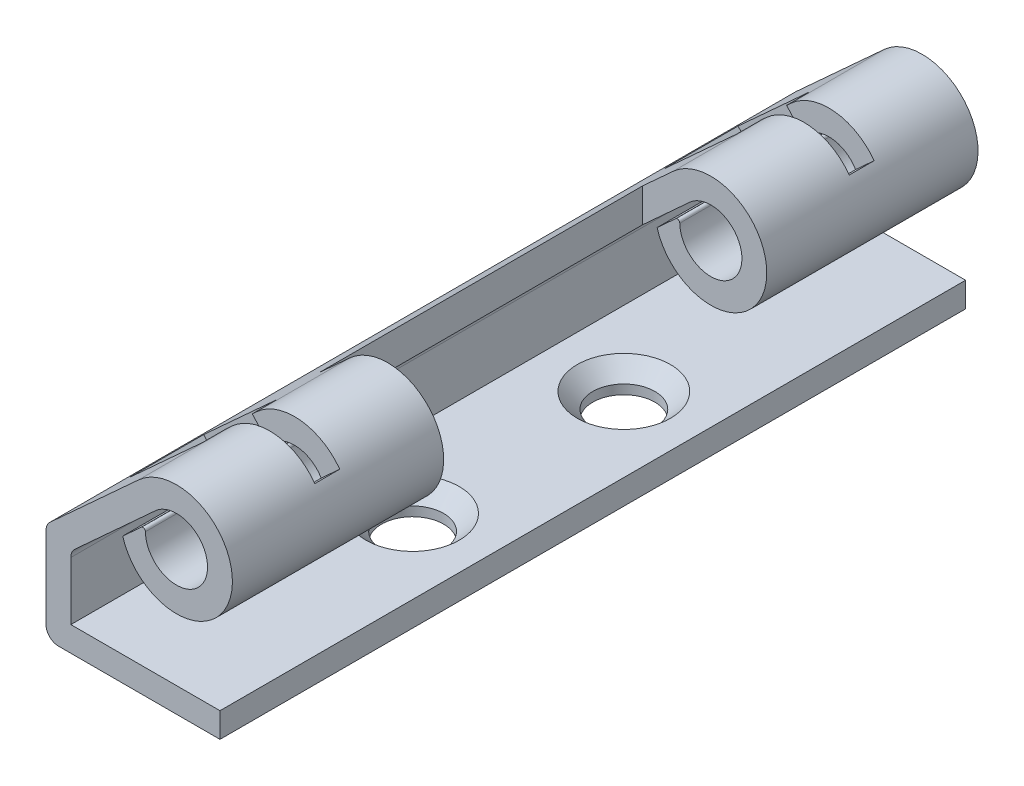
SolidWorks part; units mm, degrees
ref_plane "前视基准面" through (0, 0, 0) normal (0, 0, 1) x (1, 0, 0)
ref_plane "上视基准面" through (0, 0, 0) normal (0, 1, 0) x (1, 0, 0)
ref_plane "右视基准面" through (0, 0, 0) normal (1, 0, 0) x (0, 0, -1)
sketch "草图1" plane through (0, 0, 0) normal (0, 0, 1) x (1, 0, 0)
  line L0 (0, 0) -> (-13, 0)
  line L1 (-14, 1) -> (-14, 7.5592)
  line L2 (-13.6746, 8.2974) -> (-6.5358, 14.8217)
  line L3 (0, 2) -> (-12, 2)
  line L4 (-12, 2) -> (-12, 6.6776)
  line L5 (-11.6746, 7.4158) -> (-5.1866, 13.3454)
  line L6 (0, 2) -> (0, 0)
  line L7 (-7.8249, 10.2568) -> (-6.3348, 11.6187)
  line L8 (-12, 2) -> (-12, 7.1184) construction
  line L9 (-12, 7.1184) -> (-5.1866, 13.3454) construction
  line L10 (-14, 0) -> (-14, 8) construction
  line L11 (-14, 8) -> (-6.5358, 14.8217) construction
  line L12 (0, 0) -> (-14, 0) construction
  arc A0 (-7.8249, 10.2568) -> (-6.5358, 14.8217) centre (-3.5, 11.5) ccw
  arc A1 (-5.9999, 11.4732) -> (-5.1866, 13.3454) centre (-3.5, 11.5) ccw
  circle A2 centre (-3.5, 11.5) radius 2.5 construction
  circle A3 centre (-3.5, 11.5) radius 4.5 construction
  arc A4 (-6.3348, 11.6187) -> (-5.9999, 11.4732) centre (-6.1998, 11.471) cw
  arc A5 (-12, 6.6776) -> (-11.6746, 7.4158) centre (-11, 6.6776) cw
  arc A6 (-14, 7.5592) -> (-13.6746, 8.2974) centre (-13, 7.5592) cw
  arc A7 (-13, 0) -> (-14, 1) centre (-13, 1) cw
  point P7 (-3.5, 16)
  point P8 (1, 11.5)
  point P25 (-14, 8)
  dimension "D4" = 9
  dimension "D8" = 0.2
  dimension "D9" = 1
  dimension "D10" = 1
  dimension "D2" = 16
  dimension "D3" = 14
  dimension "D5" = 15
  dimension "D6" = 0.5
  dimension "D11" = 8
  dimension "D7" = 2
extrude "凸台-拉伸1" add sketch "草图1" along normal mid plane 60
sketch "草图2" plane through (0, 2, 0) normal (0, 1, 0) x (1, 0, 0)
  line L0 (1, -30) -> (1, 30) construction
  line L1 (1, 13) -> (-9, 13)
  line L2 (1, 13) -> (1, -13)
  line L3 (1, -13) -> (-9, -13)
  line L4 (-9, 13) -> (-9, -13)
  line L5 (-7.8249, -30) -> (1, -30) construction
  line L6 (1, 30) -> (-7.8249, 30) construction
  line L7 (-14, -30) -> (-14, 30) construction
  dimension "D1" = 17
  dimension "D2" = 17
  dimension "D3" = 5
extrude "切除-拉伸1" cut sketch "草图2" along normal up to next
hole_wizard "打孔尺寸(%根据十字)槽沉头木螺钉的类型1" positions "草图4" profile "草图3" countersink size "M4" standard "GB" end condition through all
sketch "草图4" plane through (0, 2, 0) normal (0, 1, 0) x (1, 0, 0)
  line L0 (0, -30) -> (0, 30) construction
  line L1 (0, 0) -> (-9, 0) construction
  line L2 (-9, -13) -> (-9, 13) construction
  point P0 (-6, 8.5)
  point P2 (-6, -8.5)
  dimension "D1" = 17
  dimension "D2" = 6
sketch "草图3" plane through (-6, 2, -8.5) normal (1, 0, 0) x (0, 0, 1)
  line L0 (0, 0) -> (0, 2)
  line L1 (0, 2) -> (2.5, 2)
  line L2 (2.5, 2) -> (2.5, 1.25)
  line L3 (2.5, 1.25) -> (3.75, 0)
  line L5 (3.75, 0) -> (0, 0)
  line L6 (-2.5, 1.25) -> (-3.75, 0) construction
  line L11 (0, -6.35) -> (0, 107.95) construction
  dimension "通孔孔直径" = 5
  dimension "通孔孔深度" = 2
  dimension "近端锥形沉头孔直径" = 7.5
  dimension "近端锥形沉头孔角度" = 90
sketch "草图5" plane through (-10.3555, 11.3308, 0) normal (-0.6746, 0.7382, 0) x (0.7382, 0.6746, 0)
  line L0 (9.6746, 13) -> (9.6746, 30) construction
  line L1 (-3.3254, 24.5) -> (4.6746, 24.5)
  line L2 (-3.3254, 24.5) -> (-3.3254, 18.5)
  line L3 (-3.3254, 18.5) -> (4.6746, 18.5)
  line L4 (4.6746, 24.5) -> (4.6746, 22.5)
  line L5 (4.6746, 22.5) -> (9.6746, 22.5)
  line L6 (1.8363, 13) -> (5.1746, 13) construction
  line L7 (4.6746, 20.5) -> (9.6746, 20.5)
  line L8 (9.6746, 22.5) -> (9.6746, 20.5)
  line L9 (4.6746, 20.5) -> (4.6746, 18.5)
  line L10 (0, 0) -> (-9.6596, 0) construction
  line L11 (-9.6596, -30) -> (-9.6596, 30) construction
  line L12 (9.6746, -22.5) -> (9.6746, -20.5)
  line L13 (4.6746, -20.5) -> (9.6746, -20.5)
  line L14 (4.6746, -22.5) -> (9.6746, -22.5)
  line L15 (4.6746, -24.5) -> (4.6746, -22.5)
  line L16 (4.6746, -20.5) -> (4.6746, -18.5)
  line L17 (-3.3254, -18.5) -> (4.6746, -18.5)
  line L18 (-3.3254, -24.5) -> (-3.3254, -18.5)
  line L19 (-3.3254, -24.5) -> (4.6746, -24.5)
  dimension "D1" = 6
  dimension "D2" = 8
  dimension "D3" = 5
  dimension "D4" = 2
  dimension "D5" = 2
  dimension "D6" = 5.5
extrude "切除-拉伸2" cut sketch "草图5" against normal blind 5
